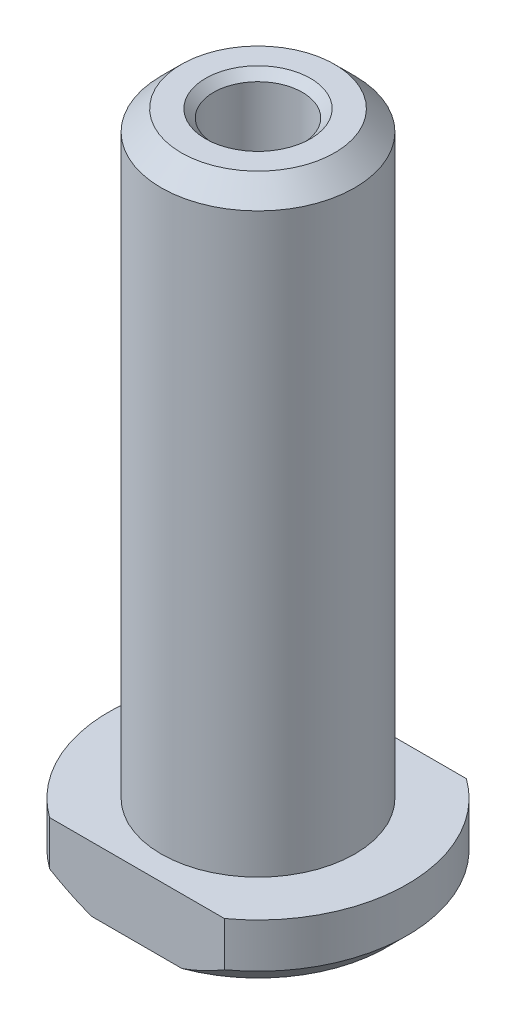
SolidWorks part; units mm, degrees
material "1023 Листовая углеродистая сталь (SS)"
ref_plane "Спереди" through (0, 0, 0) normal (0, 0, 1) x (1, 0, 0)
ref_plane "Сверху" through (0, 0, 0) normal (0, 1, 0) x (1, 0, 0)
ref_plane "Справа" through (0, 0, 0) normal (1, 0, 0) x (0, 0, -1)
ref_plane "Плоскость4" through (0, -164, 0) normal (0, -1, 0) x (1, 0, 0)
sketch "Эскиз1" plane through (0, -164, 0) normal (0, -1, 0) x (1, 0, 0)
  line L0 (21.6564, 30) -> (-21.6564, 30)
  line L1 (-21.6564, -30) -> (21.6564, -30)
  arc A0 (-21.6564, 30) -> (-21.6564, -30) centre (0, 0) ccw
  arc A1 (21.6564, -30) -> (21.6564, 30) centre (0, 0) ccw
extrude "Бобышка-Вытянуть1" add sketch "Эскиз1" against normal blind 16
ref_plane "Плоскость5" through (0, 0, 0) normal (0, 0, -1) x (-1, 0, 0)
sketch "Эскиз2" plane through (0, 0, 0) normal (0, 0, -1) x (-1, 0, 0)
  line L0 (-24, -148) -> (0, -148)
  line L1 (0, -148) -> (0, 0)
  line L2 (0, 0) -> (-24, 0)
  line L3 (-24, 0) -> (-24, -148)
  line L4 (0, -148) -> (0, 0) construction
revolve "Повернуть1" add sketch "Эскиз2" angle 360 about L4
hole_wizard "Цековка для  болта с шестигранной головкой M301" positions "Эскиз4" profile "Эскиз3" counterbore size "M30" standard "Ansi Metric"
sketch "Эскиз4" plane through (0, 0, 0) normal (0, 1, 0) x (1, 0, 0)
  point P0 (0, 0)
sketch "Эскиз3" plane through (0, 0, 0) normal (1, 0, 0) x (0, 0, 1)
  line L0 (0, 0) -> (0, 124.2376)
  line L1 (0, 124.2376) -> (16, 115)
  line L2 (16, 115) -> (16, 65)
  line L3 (16, 65) -> (11, 65)
  line L4 (11, 65) -> (11, 0)
  line L5 (11, 0) -> (0, 0)
  line L10 (0, 124.2376) -> (-16, 115) construction
  line L11 (0, -6.35) -> (0, 107.95) construction
  dimension "Диаметр отверстия" = 32
  dimension "Глубина отверстия" = 115
  dimension "Диаметр цековки" = 22
  dimension "Глубина цековки" = 65
  dimension "Угол заточки сверла" = 120
chamfer "Фаска1" distance 5 angle 45 3 edges at (0, 0, 24) (37, -164, 0) (-37, -164, 0)
chamfer "Фаска2" distance 2 angle 45 1 edges at (0, 0, 11)
